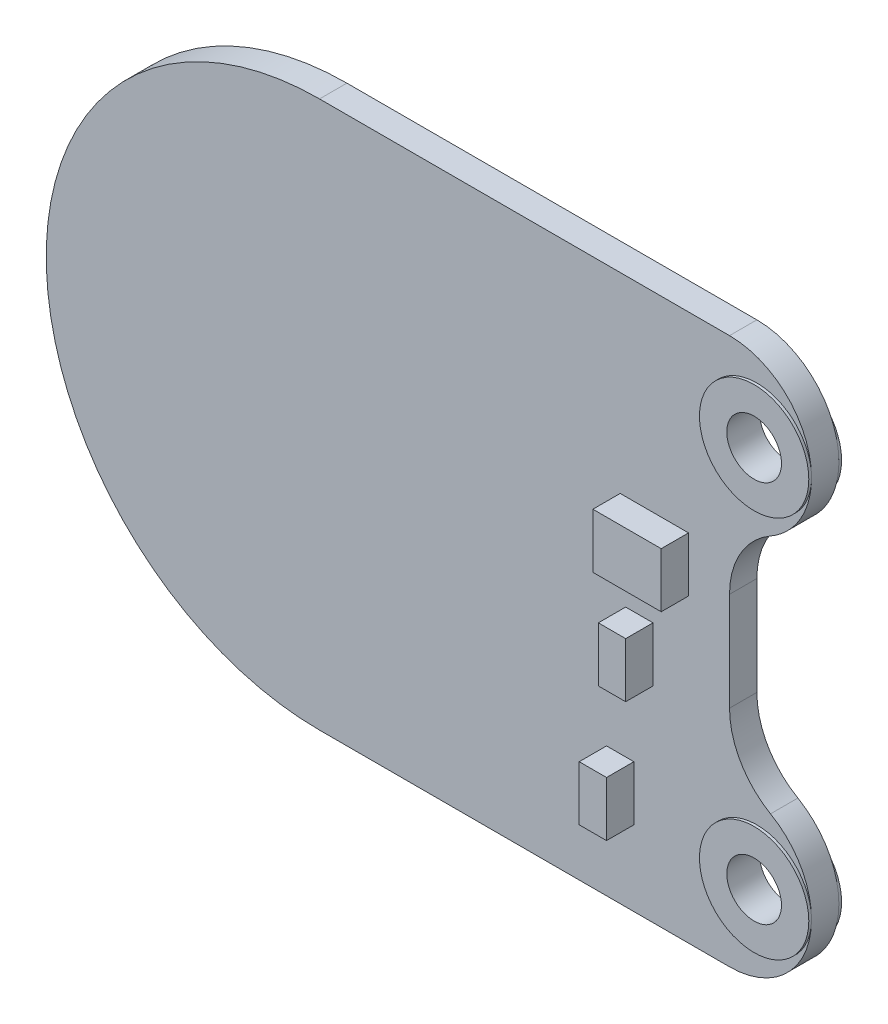
SolidWorks part; units mm, degrees
ref_plane "Front Plane" through (0, 0, 0) normal (0, 0, 1) x (1, 0, 0)
ref_plane "Top Plane" through (0, 0, 0) normal (0, 1, 0) x (1, 0, 0)
ref_plane "Right Plane" through (0, 0, 0) normal (1, 0, 0) x (0, 0, -1)
sketch "Sketch1" plane through (0, 0, 0) normal (0, 0, 1) x (1, 0, 0)
  line L0 (11, 4) -> (11, -4)
  line L1 (-4, 10) -> (11, 10)
  line L3 (-4, -10) -> (11, -10)
  line L5 (-10.563, 7.545) -> (12.9689, -9.2635) construction
  line L6 (-10.563, -7.545) -> (12.9689, 9.2635) construction
  arc A0 (-4, 10) -> (-4, -10) centre (-4, 0) ccw
  arc A1 (11, 4) -> (11, 10) centre (11, 7) ccw
  arc A2 (11, -10) -> (11, -4) centre (11, -7) ccw
  circle A5 centre (12, 7) radius 1
  circle A6 centre (12, -7) radius 1
  point P0 (0, 0)
  point P15 (-14, 0)
  dimension "D3" = 20
  dimension "D4" = 2
  dimension "D1" = 6
  dimension "D2" = 6
  dimension "D5" = 2
  dimension "D6" = 1
  dimension "D7" = 1
extrude "Boss-Extrude1" add sketch "Sketch1" along normal blind 1
fillet "Fillet1" radius 3 2 edges at (11, -4, 0.5) (11, 4, 0.5)
sketch "Sketch2" plane through (0, 0, 1) normal (0, 0, 1) x (1, 0, 0)
  circle A0 centre (12, 7) radius 2
  circle A1 centre (12, -7) radius 2
  circle A2 centre (12, 7) radius 1
  circle A3 centre (12, -7) radius 1
  dimension "D1" = 4
  dimension "D2" = 4
extrude "Boss-Extrude2" add sketch "Sketch2" along normal blind 0.1 and the other way blind 1.1 contours A0 | A1
sketch "Sketch3" plane through (0, 0, 1.1) normal (0, 0, 1) x (1, 0, 0)
  circle A0 centre (12, 7) radius 1
  circle A1 centre (12, -7) radius 1
  dimension "D1" = 2
  dimension "D2" = 2
extrude "Cut-Extrude1" cut sketch "Sketch3" against normal blind 2
sketch "Sketch4" plane through (0, 0, 1) normal (0, 0, 1) x (1, 0, 0)
  line L0 (11, 10) -> (-4, 10) construction
  line L1 (7, 3) -> (9.5, 3)
  line L2 (7, 3) -> (7, 1)
  line L3 (7, 1) -> (9.5, 1)
  line L4 (9.5, 3) -> (9.5, 1)
  line L5 (7, 3) -> (9.5, 1) construction
  line L6 (7, 1) -> (9.5, 3) construction
  line L7 (7.2, -0.5) -> (8.2, -0.5)
  line L8 (7.2, -0.5) -> (7.2, -2.5)
  line L9 (7.2, -2.5) -> (8.2, -2.5)
  line L10 (8.2, -0.5) -> (8.2, -2.5)
  line L11 (7.2, -0.5) -> (8.2, -2.5) construction
  line L12 (7.2, -2.5) -> (8.2, -0.5) construction
  line L13 (6.5, -5.25) -> (7.5, -5.25)
  line L14 (6.5, -5.25) -> (6.5, -7.25)
  line L15 (6.5, -7.25) -> (7.5, -7.25)
  line L16 (7.5, -5.25) -> (7.5, -7.25)
  line L17 (6.5, -5.25) -> (7.5, -7.25) construction
  line L18 (6.5, -7.25) -> (7.5, -5.25) construction
  line L19 (-4, -10) -> (11, -10) construction
  line L20 (11, -1.8038) -> (11, 1.8038) construction
  point P0 (8.25, 2)
  point P5 (7.7, -1.5)
  point P10 (7, -6.25)
  dimension "D1" = 2.5
  dimension "D2" = 2
  dimension "D3" = 2
  dimension "D4" = 1
  dimension "D5" = 1
  dimension "D6" = 2
  dimension "D7" = 7
  dimension "D8" = 7.5
  dimension "D9" = 2.75
  dimension "D10" = 3.5
  dimension "D11" = 2.8
  dimension "D12" = 1.5
extrude "Boss-Extrude3" add sketch "Sketch4" along normal blind 1
